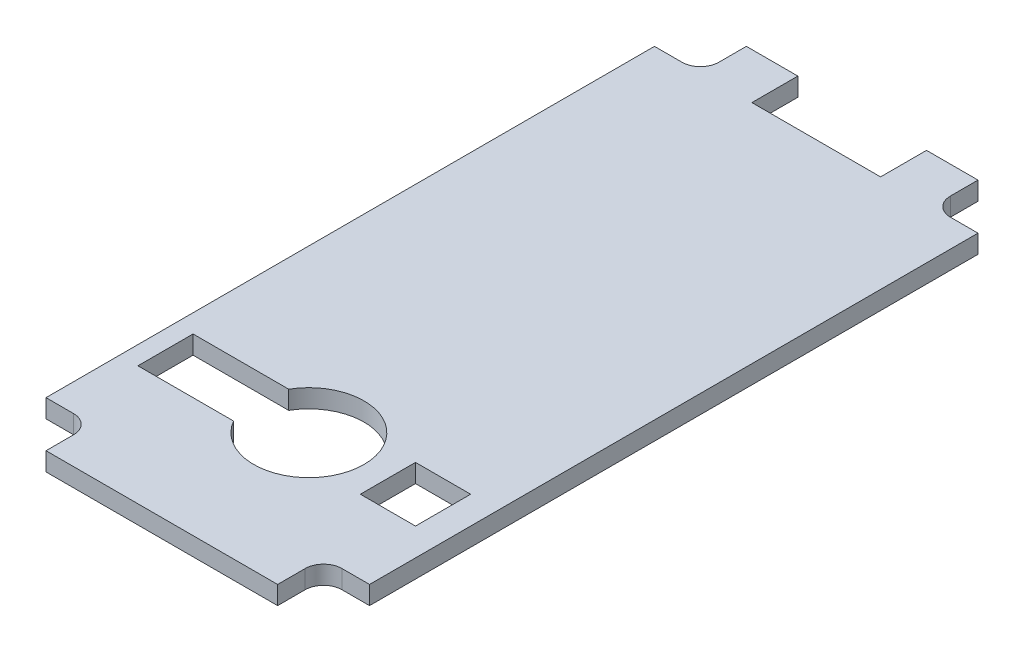
SolidWorks part; units mm, degrees
ref_plane "前基準面" through (0, 0, 0) normal (0, 0, 1) x (1, 0, 0)
ref_plane "上基準面" through (0, 0, 0) normal (0, 1, 0) x (1, 0, 0)
ref_plane "右基準面" through (0, 0, 0) normal (1, 0, 0) x (0, 0, -1)
sketch "草圖2" plane through (0, 0, 0) normal (0, 1, 0) x (1, 0, 0)
  line L1 (-8.8, 19.05) -> (8.8, 19.05)
  line L2 (-8.8, 19.05) -> (-8.8, -19.05)
  line L3 (-8.8, -19.05) -> (8.8, -19.05)
  line L4 (8.8, 19.05) -> (8.8, -19.05)
  line L5 (-8.8, 19.05) -> (8.8, -19.05) construction
  line L6 (-8.8, -19.05) -> (8.8, 19.05) construction
  point P0 (0, 0)
  dimension "D1" = 17.6
  dimension "D2" = 38.1
extrude "伸長2" add sketch "草圖2" along normal blind 1
sketch "草圖3" plane through (0, 1, 0) normal (0, 1, 0) x (1, 0, 0)
  line L0 (8.8, 19.05) -> (-8.8, 19.05) construction
  line L1 (-3.5, 16.55) -> (3.5, 16.55)
  line L2 (-3.5, 16.55) -> (-3.5, 19.05)
  line L3 (-3.5, 19.05) -> (3.5, 19.05)
  line L4 (3.5, 16.55) -> (3.5, 19.05)
  line L5 (-3.5, 16.55) -> (3.5, 19.05) construction
  line L6 (-3.5, 19.05) -> (3.5, 16.55) construction
  line L7 (0, 0) -> (0, 17.8) construction
  line L8 (6.3, 19.05) -> (6.3, -19.05) construction
  line L9 (8.8, 19.05) -> (6.3, 19.05)
  line L10 (8.8, 19.05) -> (8.8, 16.55)
  line L11 (8.8, 16.55) -> (7.3, 16.55)
  line L12 (6.3, 19.05) -> (6.3, 17.55)
  line L13 (-8.8, -19.05) -> (8.8, -19.05) construction
  line L14 (8.8, 16.55) -> (-8.8, 16.55) construction
  line L15 (-8.8, 19.05) -> (-8.8, -19.05) construction
  line L16 (-6.3, 19.05) -> (-6.3, -19.05) construction
  line L17 (-8.8, 19.05) -> (-6.3, 19.05)
  line L18 (-8.8, 19.05) -> (-8.8, 16.55)
  line L19 (-8.8, 16.55) -> (-7.3, 16.55)
  line L20 (-6.3, 19.05) -> (-6.3, 17.55)
  line L21 (-8.8, -16.55) -> (8.8, -16.55) construction
  line L22 (-8.8, -19.05) -> (-6.3, -19.05)
  line L23 (-8.8, -19.05) -> (-8.8, -16.55)
  line L24 (-8.8, -16.55) -> (-7.3, -16.55)
  line L25 (-6.3, -19.05) -> (-6.3, -17.55)
  line L26 (8.8, -19.05) -> (8.8, 19.05) construction
  line L27 (0, 0) -> (0, -19.05) construction
  line L28 (7.3, -16.55) -> (8.8, -16.55)
  line L29 (6.3, -17.55) -> (6.3, -19.05)
  line L30 (6.3, -19.05) -> (8.8, -19.05)
  line L31 (8.8, -16.55) -> (8.8, -19.05)
  line L32 (0, -11.05) -> (-8.8, -11.05) construction
  line L33 (-2.3, -9.55) -> (-2.5981, -9.55) construction
  line L34 (-7.8, -9.55) -> (-2.5981, -9.55)
  line L35 (-7.8, -9.55) -> (-7.8, -12.55)
  line L36 (-7.8, -12.55) -> (-2.5981, -12.55)
  line L37 (-2.3, -12.55) -> (-2.5981, -12.55) construction
  line L38 (-7.8, -9.55) -> (-2.3, -12.55) construction
  line L39 (-7.8, -12.55) -> (-2.3, -9.55) construction
  line L40 (-2.3, -9.55) -> (-2.3, -12.55) construction
  line L41 (-2.9305, -9.55) -> (8.8, -9.55) construction
  line L42 (-2.3, -12.55) -> (8.8, -12.55) construction
  line L44 (4.3, -9.55) -> (7.3, -9.55)
  line L45 (4.3, -9.55) -> (4.3, -12.55)
  line L46 (4.3, -12.55) -> (7.3, -12.55)
  line L47 (7.3, -9.55) -> (7.3, -12.55)
  arc A0 (-7.3, 16.55) -> (-6.3, 17.55) centre (-7.3, 17.55) ccw
  arc A1 (7.3, 16.55) -> (6.3, 17.55) centre (7.3, 17.55) cw
  arc A2 (7.3, -16.55) -> (6.3, -17.55) centre (7.3, -17.55) ccw
  arc A3 (-7.3, -16.55) -> (-6.3, -17.55) centre (-7.3, -17.55) cw
  arc A4 (-2.5981, -12.55) -> (-2.5981, -9.55) centre (0, -11.05) ccw
  point P0 (0, 17.8)
  point P39 (-6.3, 16.55)
  point P42 (6.3, 16.55)
  point P47 (-6.3, -16.55)
  point P53 (-5.05, -11.05)
  dimension "D6" = 1
  dimension "D7" = 6
  dimension "D8" = 8
  dimension "D1" = 2.5
  dimension "D2" = 7
  dimension "D3" = 2.5
  dimension "D4" = 2.5
  dimension "D5" = 2.5
  dimension "D9" = 1
  dimension "D10" = 5.5
  dimension "D11" = 3
  dimension "D12" = 3
  dimension "D13" = 1.5
extrude "伸長3" cut sketch "草圖3" against normal up to next
